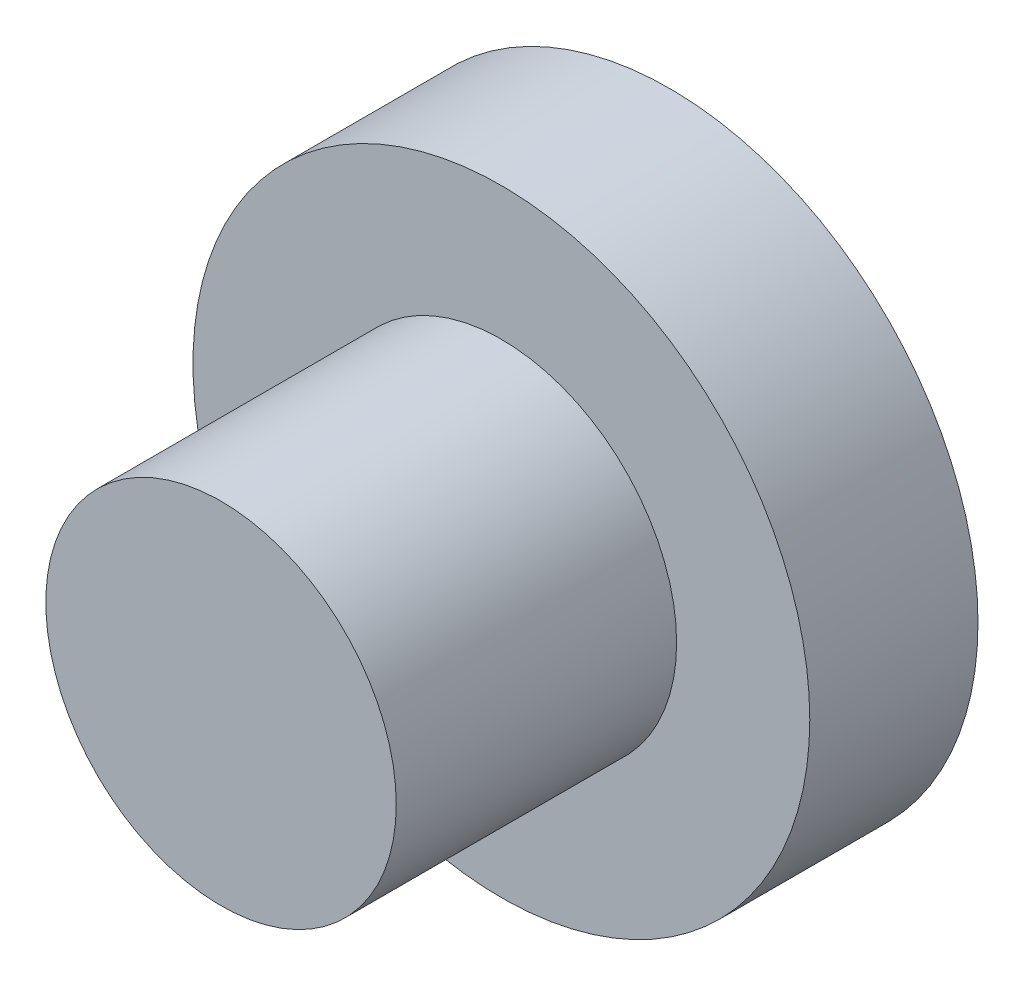
SolidWorks part; units mm, degrees
ref_plane "Front Plane" through (0, 0, 0) normal (0, 0, 1) x (1, 0, 0)
ref_plane "Top Plane" through (0, 0, 0) normal (0, 1, 0) x (1, 0, 0)
ref_plane "Right Plane" through (0, 0, 0) normal (1, 0, 0) x (0, 0, -1)
sketch "Sketch1" plane through (0, 0, 0) normal (0, 0, 1) x (1, 0, 0)
  circle A0 centre (0, 0) radius 22
  dimension "D1" = 44
extrude "Boss-Extrude1" add sketch "Sketch1" along normal blind 12
sketch "Sketch2" plane through (0, 0, 12) normal (0, 0, 1) x (1, 0, 0)
  circle A0 centre (0, 0) radius 12.5
  dimension "D1" = 25
extrude "Boss-Extrude2" add sketch "Sketch2" along normal blind 20
